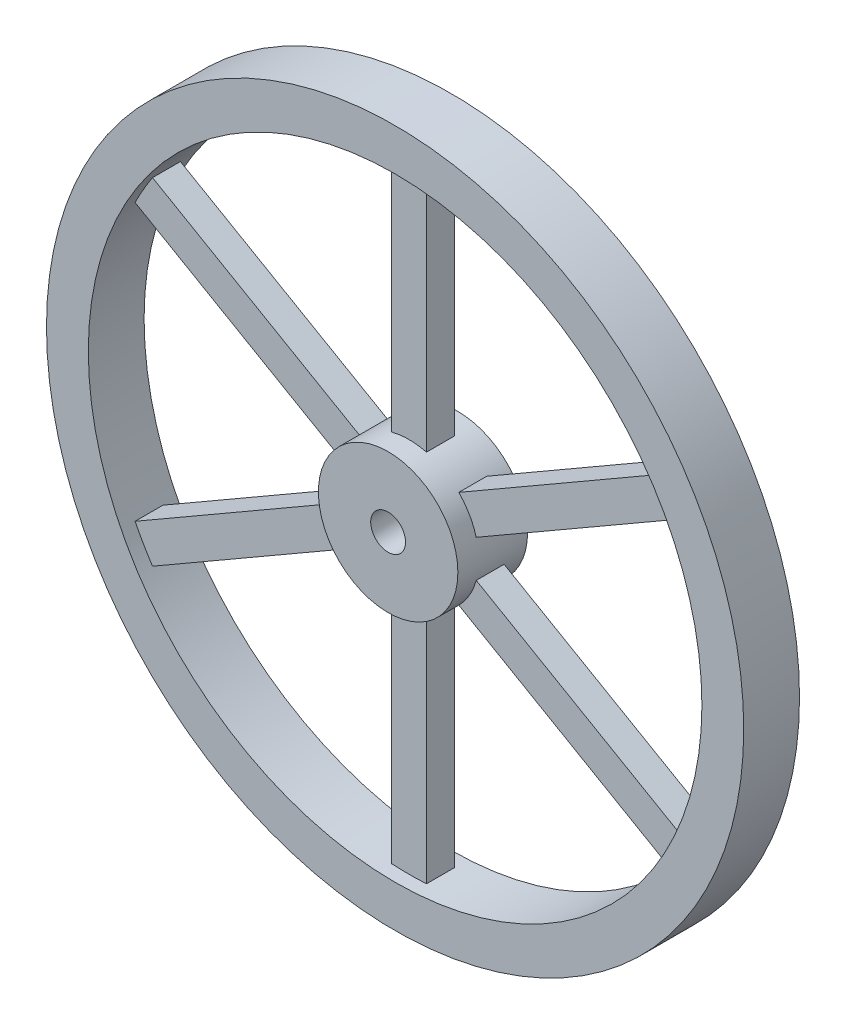
SolidWorks part; units mm, degrees
material "Gray Cast Iron"
ref_plane "Front Plane" through (0, 0, 0) normal (0, 0, 1) x (1, 0, 0)
ref_plane "Top Plane" through (0, 0, 0) normal (0, 1, 0) x (1, 0, 0)
ref_plane "Right Plane" through (0, 0, 0) normal (1, 0, 0) x (0, 0, -1)
sketch "Sketch1" plane through (0, 0, 0) normal (0, 0, 1) x (1, 0, 0)
  circle A0 centre (0, 0) radius 50
  circle A1 centre (0, 0) radius 44
  dimension "D1" = 100
  dimension "D2" = 88
extrude "Boss-Extrude1" add sketch "Sketch1" along normal mid plane 8
sketch "Sketch2" plane through (0, 0, 0) normal (0, 0, 1) x (1, 0, 0)
  circle A0 centre (0, 0) radius 10
  dimension "D1" = 20
extrude "Boss-Extrude2" add sketch "Sketch2" along normal mid plane 10
sketch "Sketch3" plane through (0, 0, 0) normal (0, 0, 1) x (1, 0, 0)
  line L0 (-2.5, 9) -> (2.5, 9)
  line L1 (2.5, 9) -> (2.5, 45)
  line L2 (2.5, 45) -> (-2.5, 45)
  line L3 (-2.5, 45) -> (-2.5, 9)
  dimension "D1" = 5
  dimension "D2" = 36
extrude "Boss-Extrude3" add sketch "Sketch3" along normal mid plane 4
sketch "Sketch4" plane through (0, 0, 0) normal (0, 0, 1) x (1, 0, 0)
  circle A0 centre (0, 0) radius 2.5
  dimension "D1" = 5
extrude "Cut-Extrude1" cut sketch "Sketch4" against normal mid plane 12
pattern_circular "CirPattern1" count 6 over 360 about axis through (0, 0, 0) along (0, 0, 1) of "Boss-Extrude3"
